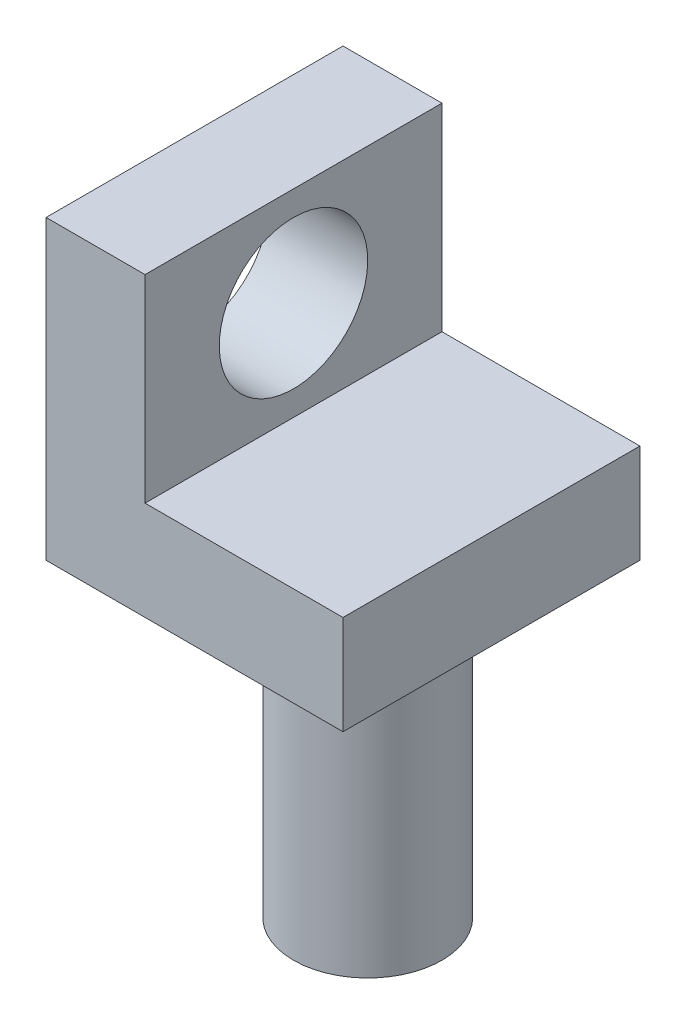
SolidWorks part; units mm, degrees
ref_plane "Front Plane" through (0, 0, 0) normal (0, 0, 1) x (1, 0, 0)
ref_plane "Top Plane" through (0, 0, 0) normal (0, 1, 0) x (1, 0, 0)
ref_plane "Right Plane" through (0, 0, 0) normal (1, 0, 0) x (0, 0, -1)
sketch "Sketch2" plane through (0, 0, 0) normal (0, 1, 0) x (1, 0, 0)
  circle A0 centre (0, 0) radius 7.5
  dimension "D1" = 15
extrude "rotaiting pin" add sketch "Sketch2" along normal blind 30
sketch "Sketch3" plane through (0, 0, 0) normal (0, 0, 1) x (1, 0, 0)
  line L0 (7.5, 30) -> (-7.5, 30) construction
  line L1 (-17.5, 60) -> (-7.5, 60)
  line L3 (-17.5, 30) -> (12.5, 30)
  line L4 (-7.5, 60) -> (-7.5, 40)
  line L5 (7.5, 0) -> (7.5, 30) construction
  line L7 (-17.5, 30) -> (-17.5, 60)
  line L8 (-7.5, 40) -> (12.5, 40)
  line L9 (12.5, 30) -> (12.5, 40)
  point P1 (-19.3855, 36.4273)
  point P7 (0, 0)
  point P10 (0, 0)
  point P11 (9.3638, 30)
  point P12 (-19.4697, 36.4273)
  point P13 (-19.3855, 43.9198)
  dimension "D1" = 30
  dimension "D2" = 10
  dimension "D3" = 5
  dimension "D4" = 30
  dimension "D5" = 10
extrude "body " add sketch "Sketch3" along normal mid plane 30
sketch "Sketch4" plane through (-7.5, 0, 0) normal (1, 0, 0) x (0, 0, -1)
  line L0 (-15, 60) -> (15, 60) construction
  circle A0 centre (0, 50) radius 7.5
  point P2 (0, 0)
  dimension "D1" = 15
  dimension "D2" = 10
extrude "hole" cut sketch "Sketch4" against normal blind 30
